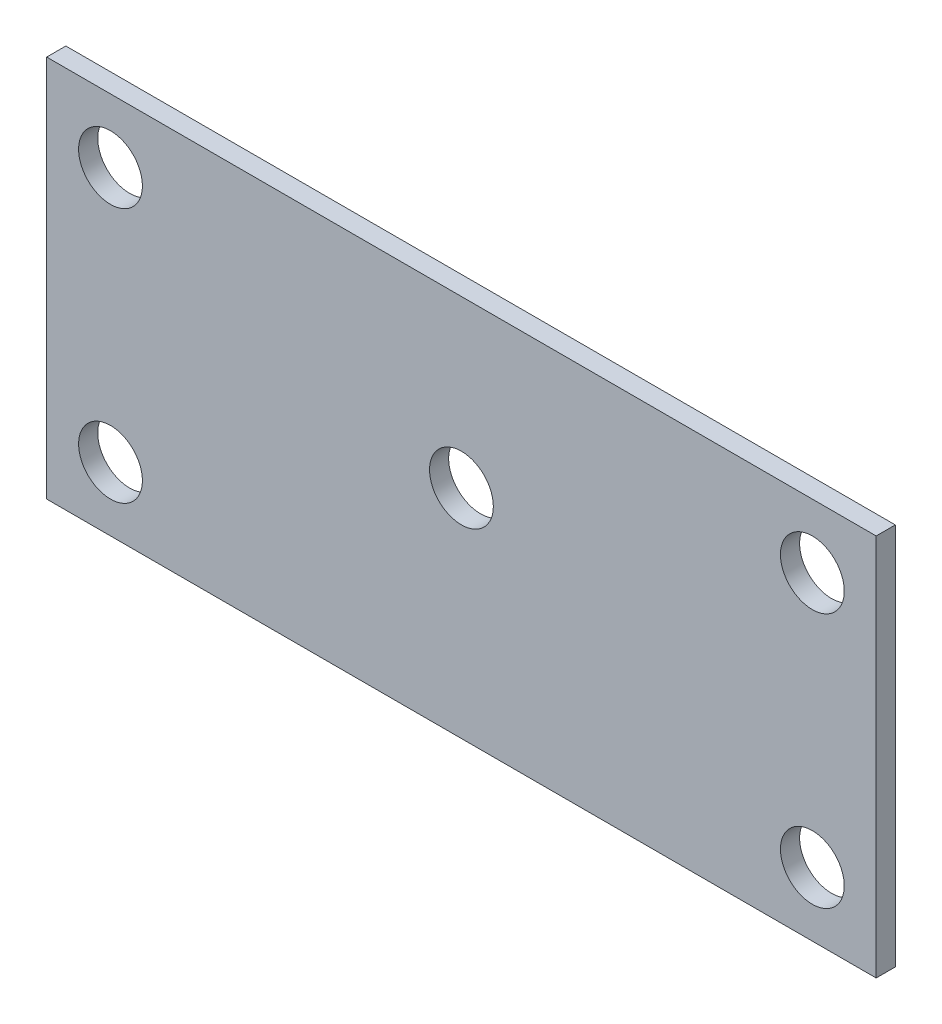
SolidWorks part; units mm, degrees
ref_plane "Plan de face" through (0, 0, 0) normal (0, 0, 1) x (1, 0, 0)
ref_plane "Plan de dessus" through (0, 0, 0) normal (0, 1, 0) x (1, 0, 0)
ref_plane "Plan de droite" through (0, 0, 0) normal (1, 0, 0) x (0, 0, -1)
sketch "Esquisse1" plane through (0, 0, 0) normal (0, 0, 1) x (1, 0, 0)
  line L0 (45, 60) -> (45, 0)
  line L1 (0, 0) -> (90, 0)
  line L2 (0, 0) -> (0, 60)
  line L3 (0, 60) -> (90, 60)
  line L4 (90, 0) -> (90, 60)
  line L5 (0, 40) -> (-20, 40) construction
  line L6 (90, 0) -> (90, 60)
  line L7 (0, 20) -> (-20, 20) construction
  line L8 (-20, 60) -> (0, 40) construction
  line L9 (0, 0) -> (-20, 0)
  line L10 (0, 0) -> (0, 60)
  line L11 (0, 60) -> (-20, 60)
  line L12 (-20, 0) -> (-20, 60)
  line L13 (-20, 0) -> (0, 20) construction
  circle A0 centre (-10, 50) radius 5
  circle A1 centre (-10, 10) radius 5
  circle A2 centre (45, 34) radius 5
  point P17 (29.9269, 40)
  point P18 (-10, 10)
  point P19 (45, 30)
  point P20 (-10, 50)
  dimension "D6" = 10
  dimension "D7" = 10
  dimension "D8" = 10
  dimension "D1" = 60
  dimension "D2" = 90
  dimension "D3" = 20
  dimension "D4" = 20
  dimension "D5" = 20
  dimension "D9" = 4
extrude "Boss.-Extru.1" add sketch "Esquisse1" along normal blind 3 contours L3 L2 L1 L0 | L12 L9 L2 L11 A1 A0
mirror "Symétrie1" about plane through (45, 0, 3) normal (1, 0, 0) of "Boss.-Extru.1"
